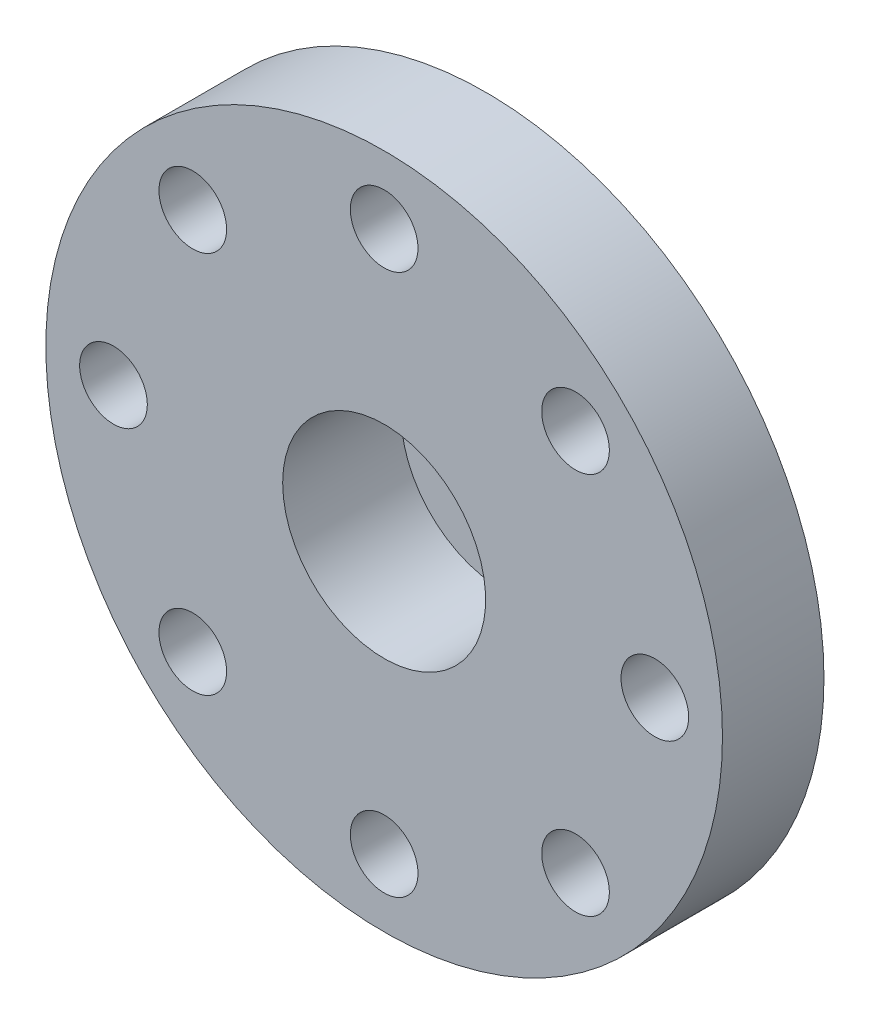
SolidWorks part; units mm, degrees
material "6061 合金"
ref_plane "前视基准面" through (0, 0, 0) normal (0, 0, 1) x (1, 0, 0)
ref_plane "上视基准面" through (0, 0, 0) normal (0, 1, 0) x (1, 0, 0)
ref_plane "右视基准面" through (0, 0, 0) normal (1, 0, 0) x (0, 0, -1)
sketch "草图1" plane through (0, 0, 0) normal (0, 0, 1) x (1, 0, 0)
  line L0 (0, 0) -> (0, 16) construction
  line L1 (0, 16) -> (0, -19.3956) construction
  line L2 (0, -19.3956) -> (0, 0) construction
  line L3 (0, 0) -> (-16.7859, 0) construction
  line L4 (-16.7859, 0) -> (19.82, 0) construction
  line L5 (19.82, 0) -> (19.82, -0.2042) construction
  circle A0 centre (0, 0) radius 10
  circle A1 centre (0, 0) radius 1.5
  circle A2 centre (0, 8) radius 1
  circle A6 centre (5.6569, 5.6569) radius 1
  circle A7 centre (8, 0) radius 1
  circle A8 centre (5.6569, -5.6569) radius 1
  circle A9 centre (0, -8) radius 1
  circle A10 centre (-5.6569, -5.6569) radius 1
  circle A11 centre (-8, 0) radius 1
  circle A12 centre (-5.6569, 5.6569) radius 1
  point P27 (0, 0)
  dimension "D1" = 8
  dimension "D2" = 8
  dimension "D3" = 3
  dimension "D4" = 20
  dimension "D5" = 2
extrude "凸台-拉伸1" add sketch "草图1" along normal blind 3
sketch "草图2" plane through (0, 0, 0) normal (0, 0, -1) x (-1, 0, 0)
  circle A0 centre (0, 0) radius 4.5
extrude "凸台-拉伸2" add sketch "草图2" along normal blind 2
sketch "草图3" plane through (0, 0, 3) normal (0, 0, -1) x (-1, 0, 0)
  circle A0 centre (0, 0) radius 3
extrude "切除-拉伸1" cut sketch "草图3" along normal blind 3.5
sketch "草图4" plane through (0, 0, -2) normal (0, 0, -1) x (-1, 0, 0)
  circle A0 centre (0, 0) radius 1.5
  dimension "D1" = 3
extrude "切除-拉伸2" cut sketch "草图4" against normal blind 10
